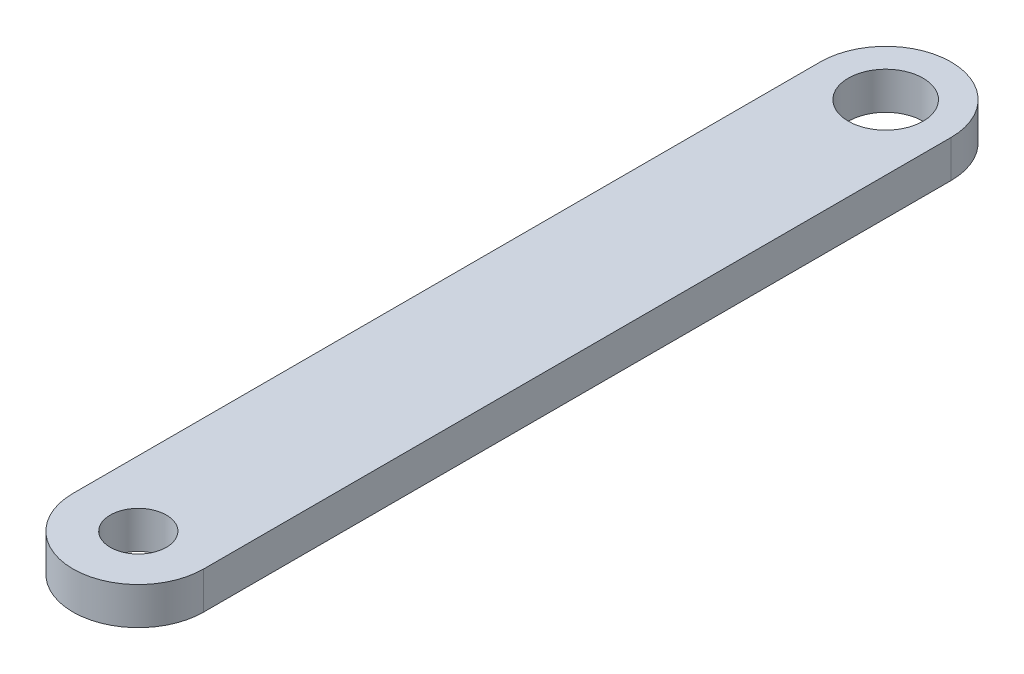
SolidWorks part; units mm, degrees
ref_plane "Front Plane" through (0, 0, 0) normal (0, 0, 1) x (1, 0, 0)
ref_plane "Top Plane" through (0, 0, 0) normal (0, 1, 0) x (1, 0, 0)
ref_plane "Right Plane" through (0, 0, 0) normal (1, 0, 0) x (0, 0, -1)
sketch "Sketch1" plane through (0, 0, 0) normal (0, 1, 0) x (1, 0, 0)
  line L0 (0, 20) -> (0, -20) construction
  line L1 (3.5, 20) -> (3.5, -20)
  line L2 (-3.5, 20) -> (-3.5, -20)
  arc A0 (3.5, 20) -> (-3.5, 20) centre (0, 20) ccw
  arc A1 (-3.5, -20) -> (3.5, -20) centre (0, -20) ccw
  circle A2 centre (0, 20) radius 2
  circle A3 centre (0, -20) radius 1.5
  point P3 (0, 0)
  dimension "D1" = 4
  dimension "D2" = 3.5
  dimension "D4" = 3
  dimension "D3" = 40
extrude "Boss-Extrude1" add sketch "Sketch1" along normal blind 2
